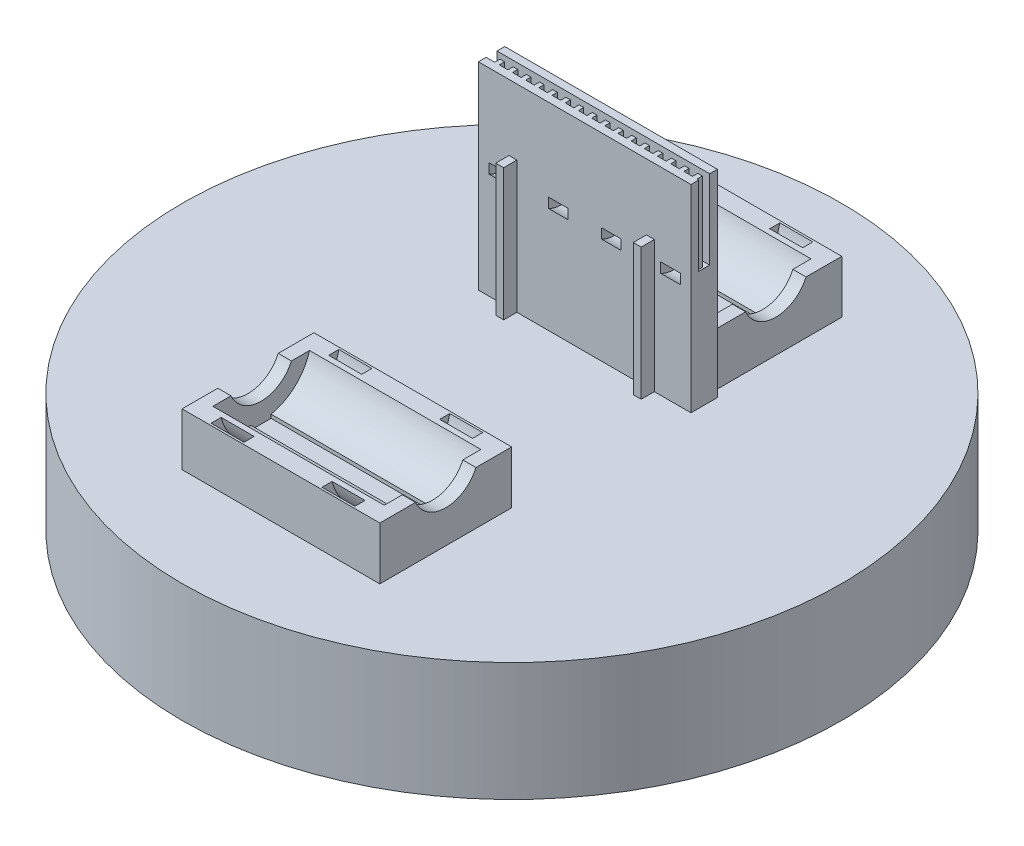
SolidWorks part; units mm, degrees
ref_plane "Ebene vorne" through (0, 0, 0) normal (0, 0, 1) x (1, 0, 0)
ref_plane "Ebene oben" through (0, 0, 0) normal (0, 1, 0) x (1, 0, 0)
ref_plane "Ebene rechts" through (0, 0, 0) normal (1, 0, 0) x (0, 0, -1)
sketch "Skizze1" plane through (0, 10, 0) normal (0, 1, 0) x (1, 0, 0)
  circle A0 centre (0, 0) radius 50
  dimension "D1" = 100
extrude "Aufsatz-Linear austragen1" add sketch "Skizze1" along normal blind 1.6 and the other way blind 16.4
sketch "Skizze2" plane through (0, 11.6, 0) normal (0, 1, 0) x (1, 0, 0)
  line L1 (-15, 35.04) -> (15, 35.04)
  line L2 (-15, 35.04) -> (-15, 15.04)
  line L3 (-15, 15.04) -> (15, 15.04)
  line L4 (15, 35.04) -> (15, 15.04)
  line L5 (-15, 35.04) -> (15, 15.04) construction
  line L6 (-15, 15.04) -> (15, 35.04) construction
  point P0 (0, 25.04)
  dimension "D1" = 30
  dimension "D2" = 20
  dimension "D3" = 25.04
extrude "Aufsatz-Linear austragen2" add sketch "Skizze2" along normal blind 8
sketch "Skizze3" plane through (-15, 0, 0) normal (-1, 0, 0) x (0, 0, 1)
  line L0 (-35.04, 19.6) -> (-15.04, 19.6) construction
  line L1 (-35.04, 11.6) -> (-15.04, 11.6) construction
  point P0 (-25.04, 21.6)
  point P4 (-25.04, 19.6)
  dimension "D1" = 10
ref_axis "Achse1" through (-15, 21.6, -25.04) along (1, 0, 0)
sketch "Skizze4" plane through (-15, 0, 0) normal (-1, 0, 0) x (0, 0, 1)
  circle A0 centre (-25.04, 21.6) radius 7.6
  dimension "D1" = 15.2
extrude "Schnitt-Linear austragen1" cut sketch "Skizze4" against normal through all
sketch "Skizze5" plane through (-15, 0, 0) normal (-1, 0, 0) x (0, 0, 1)
  line L0 (-32.3721, 19.6) -> (-17.7079, 19.6)
  arc A0 (-32.3721, 19.6) -> (-17.7079, 19.6) centre (-25.04, 21.6) ccw
  arc A1 (-29.6226, 19.6) -> (-20.4574, 19.6) centre (-25.04, 21.6) ccw
  arc M5 (-17.7079, 19.6) -> (-32.3721, 19.6) centre (-25.04, 21.6) cw
  dimension "D1" = 10
extrude "Aufsatz-Linear austragen3" add sketch "Skizze5" against normal blind 2 contours A1 L0 M5
ref_plane "Ebene1" through (0, 0, 0) normal (1, 0, 0) x (0, 0, -1)
mirror "Spiegeln1" about plane through (0, 0, 0) normal (1, 0, 0) of "Aufsatz-Linear austragen3"
sketch "Skizze7" plane through (0, 0, 0) normal (1, 0, 0) x (0, 0, -1)
  line L1 (23.54, 14.4) -> (26.54, 14.4)
  line L2 (23.54, 14.4) -> (23.54, 13.6)
  line L3 (23.54, 13.6) -> (26.54, 13.6)
  line L4 (26.54, 14.4) -> (26.54, 13.6)
  line L5 (23.54, 14.4) -> (26.54, 13.6) construction
  line L6 (23.54, 13.6) -> (26.54, 14.4) construction
  arc A0 (17.7079, 19.6) -> (32.3721, 19.6) centre (25.04, 21.6) ccw construction
  point P0 (25.04, 14)
  dimension "D1" = 3
  dimension "D2" = 0.8
extrude "Schnitt-Linear austragen2" cut sketch "Skizze7" against normal up to vertex (13 mm away) and the other way up to vertex (13 mm away)
ref_plane "Ebene2" through (0, 0, -25.04) normal (0, 0, 1) x (1, 0, 0)
sketch "Skizze6" plane through (0, 0, -25.04) normal (0, 0, 1) x (1, 0, 0)
  line L1 (-10.9122, 31.5) -> (-5.9122, 31.5)
  line L2 (-10.9122, 31.5) -> (-10.9122, 30)
  line L3 (-10.9122, 30) -> (-5.9122, 30)
  line L4 (-5.9122, 31.5) -> (-5.9122, 30)
  line L5 (-10.9122, 31.5) -> (-5.9122, 30) construction
  line L6 (-10.9122, 30) -> (-5.9122, 31.5) construction
  point P0 (-8.4122, 30.75)
  dimension "D1" = 5
  dimension "D2" = 1.5
  dimension "D3" = 8.4
revolve "Schnitt-Rotation2" cut sketch "Skizze6" angle 360 about axis through (-15, 21.6, -25.04) along (1, 0, 0)
mirror "Spiegeln2" about plane through (0, 0, 0) normal (1, 0, 0) of "Schnitt-Rotation2"
sketch "Skizze8" plane through (0, 11.6, 0) normal (0, 1, 0) x (1, 0, 0)
  point P0 (0, 0)
ref_plane "Ebene3" through (0, 0, 0) normal (0, 0, 1) x (1, 0, 0)
mirror "Spiegeln3" about plane through (0, 0, 0) normal (0, 0, 1) of "Spiegeln2", "Schnitt-Rotation2", "Schnitt-Linear austragen2", "Spiegeln1", "Aufsatz-Linear austragen3", "Schnitt-Linear austragen1", "Aufsatz-Linear austragen2"
sketch "Skizze9" plane through (0, 11.6, 0) normal (0, 1, 0) x (1, 0, 0)
  line L0 (-15, 15.04) -> (15, 15.04) construction
  line L1 (-16.1263, 15.04) -> (16.1263, 15.04)
  line L2 (-16.1263, 15.04) -> (-16.1263, 11.04)
  line L3 (-16.1263, 11.04) -> (16.1263, 11.04)
  line L4 (16.1263, 15.04) -> (16.1263, 11.04)
  line L5 (-16.1263, 15.04) -> (16.1263, 11.04) construction
  line L6 (-16.1263, 11.04) -> (16.1263, 15.04) construction
  point P0 (0, 13.04)
  dimension "D2" = 4
extrude "Aufsatz-Linear austragen4" add sketch "Skizze9" along normal blind 30
sketch "Skizze10" plane through (0, 41.6, 0) normal (0, 1, 0) x (1, 0, 0)
  line L0 (-16.1263, 12.215) -> (-14.8263, 12.215)
  line L1 (-14.8263, 12.215) -> (-14.8263, 13.015)
  line L2 (-14.8263, 13.015) -> (-14.1263, 13.015)
  line L3 (-14.1263, 13.015) -> (-14.1263, 12.215)
  line L4 (-14.1263, 12.215) -> (-12.8263, 12.215)
  line L5 (-12.8263, 12.215) -> (-12.8263, 13.015)
  line L6 (-12.8263, 13.015) -> (-12.1263, 13.015)
  line L8 (-12.1263, 13.015) -> (-12.1263, 12.215)
  line L9 (-16.1263, 13.065) -> (-16.1263, 12.215)
  line L10 (-16.1263, 15.04) -> (-16.1263, 11.04) construction
  line L11 (-12.1263, 12.215) -> (-10.8263, 12.215)
  line L12 (-10.8263, 12.215) -> (-10.8263, 13.015)
  line L13 (-10.1263, 13.015) -> (-10.1263, 12.215)
  line L14 (-10.1263, 12.215) -> (-8.8263, 12.215)
  line L15 (-8.8263, 12.215) -> (-8.8263, 13.015)
  line L16 (-8.1263, 13.015) -> (-8.1263, 12.215)
  line L17 (-8.8263, 13.015) -> (-8.1263, 13.015)
  line L18 (-10.8263, 13.015) -> (-10.1263, 13.015)
  line L19 (-8.1263, 12.215) -> (-6.8263, 12.215)
  line L20 (-6.8263, 12.215) -> (-6.8263, 13.015)
  line L21 (-6.1263, 13.015) -> (-6.1263, 12.215)
  line L22 (-6.1263, 12.215) -> (-4.8263, 12.215)
  line L23 (-4.8263, 12.215) -> (-4.8263, 13.015)
  line L24 (-4.1263, 13.015) -> (-4.1263, 12.215)
  line L25 (-4.8263, 13.015) -> (-4.1263, 13.015)
  line L26 (-6.8263, 13.015) -> (-6.1263, 13.015)
  line L27 (-4.1263, 12.215) -> (-2.8263, 12.215)
  line L28 (-2.8263, 12.215) -> (-2.8263, 13.015)
  line L29 (-2.1263, 13.015) -> (-2.1263, 12.215)
  line L30 (-2.1263, 12.215) -> (-0.8263, 12.215)
  line L31 (-0.8263, 12.215) -> (-0.8263, 13.015)
  line L32 (-0.1263, 13.015) -> (-0.1263, 12.215)
  line L33 (-0.8263, 13.015) -> (-0.1263, 13.015)
  line L34 (-2.8263, 13.015) -> (-2.1263, 13.015)
  line L35 (-0.1263, 12.215) -> (1.1737, 12.215)
  line L36 (1.1737, 12.215) -> (1.1737, 13.015)
  line L37 (1.8737, 13.015) -> (1.8737, 12.215)
  line L38 (1.8737, 12.215) -> (3.1737, 12.215)
  line L39 (3.1737, 12.215) -> (3.1737, 13.015)
  line L40 (3.8737, 13.015) -> (3.8737, 12.215)
  line L41 (3.1737, 13.015) -> (3.8737, 13.015)
  line L42 (1.1737, 13.015) -> (1.8737, 13.015)
  line L43 (3.8737, 12.215) -> (5.1737, 12.215)
  line L44 (5.1737, 12.215) -> (5.1737, 13.015)
  line L45 (5.8737, 13.015) -> (5.8737, 12.215)
  line L46 (5.8737, 12.215) -> (7.1737, 12.215)
  line L47 (7.1737, 12.215) -> (7.1737, 13.015)
  line L48 (7.8737, 13.015) -> (7.8737, 12.215)
  line L49 (7.1737, 13.015) -> (7.8737, 13.015)
  line L50 (5.1737, 13.015) -> (5.8737, 13.015)
  line L51 (7.8737, 12.215) -> (9.1737, 12.215)
  line L52 (9.1737, 12.215) -> (9.1737, 13.015)
  line L53 (9.8737, 13.015) -> (9.8737, 12.215)
  line L54 (9.8737, 12.215) -> (11.1737, 12.215)
  line L55 (11.1737, 12.215) -> (11.1737, 13.015)
  line L56 (11.8737, 13.015) -> (11.8737, 12.215)
  line L57 (11.1737, 13.015) -> (11.8737, 13.015)
  line L58 (9.1737, 13.015) -> (9.8737, 13.015)
  line L59 (11.8737, 12.215) -> (13.1737, 12.215)
  line L60 (13.1737, 12.215) -> (13.1737, 13.015)
  line L61 (13.8737, 13.015) -> (13.8737, 12.215)
  line L62 (13.8737, 12.215) -> (15.1737, 12.215)
  line L63 (15.1737, 12.215) -> (15.1737, 13.015)
  line L64 (15.8737, 13.015) -> (15.8737, 12.215)
  line L65 (15.1737, 13.015) -> (15.8737, 13.015)
  line L66 (13.1737, 13.015) -> (13.8737, 13.015)
  line L67 (15.8737, 12.215) -> (17.1737, 12.215)
  line L68 (17.1737, 12.215) -> (17.1737, 13.865)
  line L69 (17.1737, 13.865) -> (-16.1263, 13.865)
  line L70 (-16.1263, 13.865) -> (-16.1263, 13.065)
  line L71 (16.1263, 11.04) -> (16.1263, 15.04) construction
  line L75 (17.1737, 12.215) -> (17.1737, 13.015) [skipped]
  line L76 (17.8737, 13.015) -> (17.8737, 12.215) [skipped]
  line L77 (17.8737, 12.215) -> (19.1737, 12.215) [skipped]
  line L78 (19.1737, 12.215) -> (19.1737, 13.015) [skipped]
  line L79 (19.8737, 13.015) -> (19.8737, 12.215) [skipped]
  line L80 (19.1737, 13.015) -> (19.8737, 13.015) [skipped]
  line L81 (17.1737, 13.015) -> (17.8737, 13.015) [skipped]
  point P9 (-14.4763, 13.015)
  point P10 (-12.4763, 13.015)
  point P12 (16.1263, 13.04)
  point P35 (17.1737, 13.04)
  dimension "D1" = 0.8
  dimension "D2" = 2
  dimension "D3" = 0.7
  dimension "D4" = 0.85
  dimension "D6" = 1.65
  dimension "D5" = 9
extrude "Schnitt-Linear austragen3" cut sketch "Skizze10" against normal blind 12
sketch "Skizze11" plane through (0, 11.6, 0) normal (0, 1, 0) x (1, 0, 0)
  line L0 (-16.1263, 11.04) -> (16.1263, 11.04) construction
  line L1 (-11.4916, 9.04) -> (-10.2916, 9.04)
  line L2 (-11.4916, 9.04) -> (-11.4916, 11.04)
  line L3 (-11.4916, 11.04) -> (-10.2916, 11.04)
  line L4 (-10.2916, 9.04) -> (-10.2916, 11.04)
  line L5 (-11.4916, 9.04) -> (-10.2916, 11.04) construction
  line L6 (-11.4916, 11.04) -> (-10.2916, 9.04) construction
  line L8 (9.3666, 9.04) -> (10.5666, 9.04)
  line L9 (9.3666, 9.04) -> (9.3666, 11.04)
  line L10 (9.3666, 11.04) -> (10.5666, 11.04)
  line L11 (10.5666, 9.04) -> (10.5666, 11.04)
  line L12 (9.3666, 9.04) -> (10.5666, 11.04) construction
  line L13 (9.3666, 11.04) -> (10.5666, 9.04) construction
  point P0 (-10.8916, 10.04)
  point P7 (9.9666, 10.04)
  dimension "D1" = 2
  dimension "D2" = 1.2
  dimension "D3" = 2
  dimension "D4" = 1.2
extrude "Aufsatz-Linear austragen5" add sketch "Skizze11" along normal blind 20
sketch "Skizze12" plane through (-16.1263, 0, 0) normal (-1, 0, 0) x (0, 0, 1)
  line L0 (-13.865, 29.6) -> (-12.215, 29.6) construction
  point P0 (-13.04, 31.1)
  point P4 (-13.04, 29.6)
  dimension "D1" = 1.5
ref_axis "Achse2" through (-16.1263, 31.1, -13.04) along (1, 0, 0)
ref_plane "Ebene4" through (0, 31.1, 0) normal (0, 1, 0) x (1, 0, 0)
sketch "Skizze13" plane through (0, 31.1, 0) normal (0, 1, 0) x (1, 0, 0)
  line L1 (-14.5263, 17.04) -> (-11.5263, 17.04)
  line L2 (-14.5263, 17.04) -> (-14.5263, 15.84)
  line L3 (-14.5263, 15.84) -> (-11.5263, 15.84)
  line L4 (-11.5263, 17.04) -> (-11.5263, 15.84)
  line L5 (-14.5263, 17.04) -> (-11.5263, 15.84) construction
  line L6 (-14.5263, 15.84) -> (-11.5263, 17.04) construction
  line L7 (-16.1263, 15.04) -> (-16.1263, 11.04) construction
  line L11 (-15, 15.04) -> (15, 15.04) construction
  point P0 (-12.6263, 15.04)
  dimension "D1" = 1.6
  dimension "D2" = 3
  dimension "D3" = 1.2
  dimension "D4" = 0.8
revolve "Schnitt-Rotation3" cut sketch "Skizze13" angle 180 about axis through (-16.1263, 31.1, -13.04) along (1, 0, 0)
pattern_linear "Lineares Muster1" count 2 spacing 9 along (1, 0, 0) of "Schnitt-Rotation3"
mirror "Spiegeln4" about plane through (0, 0, 0) normal (1, 0, 0) of "Lineares Muster1", "Schnitt-Rotation3"
